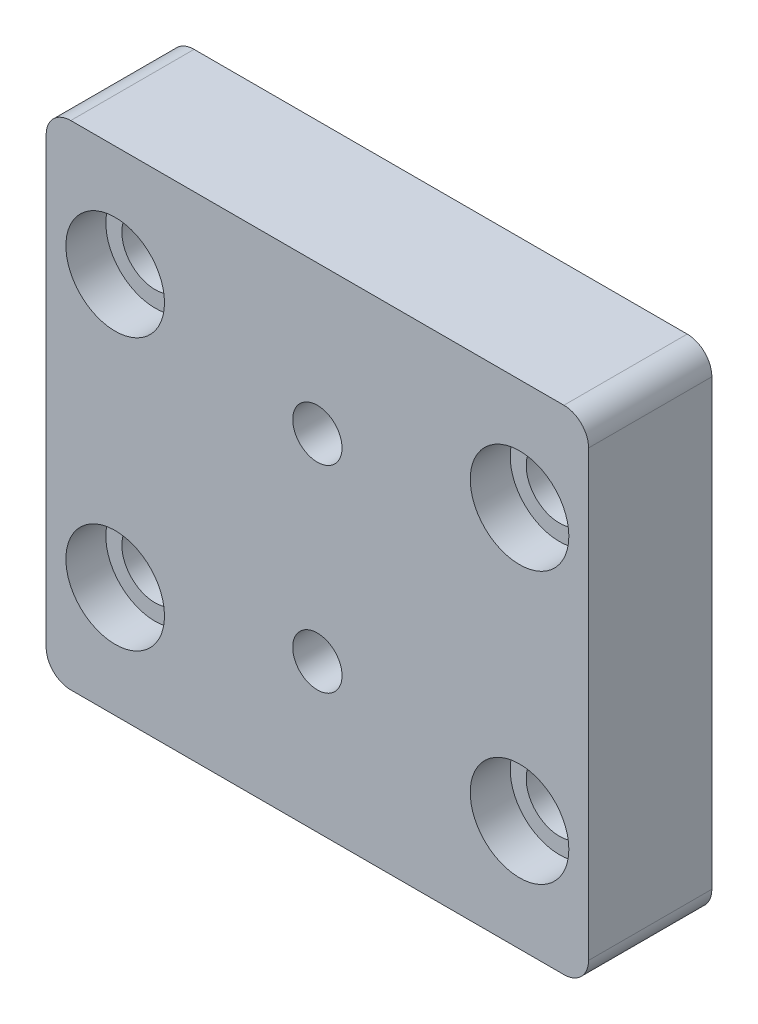
SolidWorks part; units mm, degrees
material "Masterteil Geometrie"
ref_plane "Vorne" through (0, 0, 0) normal (0, 0, 1) x (1, 0, 0)
ref_plane "Oben" through (0, 0, 0) normal (0, 1, 0) x (1, 0, 0)
ref_plane "Rechts" through (0, 0, 0) normal (1, 0, 0) x (0, 0, -1)
sketch "Skizze1" plane through (0, 0, 0) normal (0, 0, 1) x (1, 0, 0)
  line L1 (-55, -50) -> (55, -50)
  line L2 (-55, -50) -> (-55, 50)
  line L3 (-55, 50) -> (55, 50)
  line L4 (55, -50) -> (55, 50)
  line L5 (-55, -50) -> (55, 50) construction
  line L6 (-55, 50) -> (55, -50) construction
  point P0 (0, 0)
  dimension "D1" = 100
  dimension "D2" = 110
extrude "Aufsatz-Linear austragen1" add sketch "Skizze1" along normal blind 25
fillet "Verrundung1" radius 5 4 edges at (-55, -50, 12.5) (55, -50, 12.5) (-55, 50, 12.5) (55, 50, 12.5)
hole_wizard "Stirnsenkung für M12 Zylinderschraube mit Innensechskant1" positions "Skizze2" profile "Skizze3" counterbore size "M12" standard "Gabler-Normteile" end condition through all
sketch "Skizze2" plane through (0, 0, 25) normal (0, 0, 1) x (1, 0, 0)
  line L0 (-41, 27.5) -> (41, -27.5) construction
  line L1 (41, -27.5) -> (-41, -27.5) construction
  line L2 (-41, -27.5) -> (41, 27.5) construction
  point P0 (-41, 27.5)
  point P2 (41, 27.5)
  point P4 (41, -27.5)
  point P6 (-41, -27.5)
  point P16 (0, 0)
  point P20 (0, 0)
  point P22 (0, -27.5)
  dimension "D1" = 55
  dimension "D2" = 82
sketch "Skizze3" plane through (-41, 27.5, 25) normal (1, 0, 0) x (0, -1, 0)
  line L0 (0, 0) -> (0, 25)
  line L1 (0, 25) -> (6.75, 25)
  line L3 (6.75, 25) -> (6.75, 8.1)
  line L4 (6.75, 8.1) -> (10, 8.1)
  line L5 (10, 8.1) -> (10, 0)
  line L7 (10, 0) -> (0, 0)
  line L11 (0, -6.35) -> (0, 107.95) construction
  dimension "Bohrerdurchmesser" = 13.5
  dimension "Bohrungstiefe" = 25
  dimension "Senkdurchmesser2" = 20
  dimension "Senktiefe2" = 8.1
hole_wizard "Ø10.0mm Stiftloch1" positions "Skizze4" profile "Skizze5" hole size "Ø10.0" standard "Gabler-Normteile"
sketch "Skizze4" plane through (0, 0, 25) normal (0, 0, 1) x (1, 0, 0)
  line L0 (-50, -50) -> (50, -50) construction
  point P0 (0, 20)
  point P2 (0, -20)
  dimension "D1" = 30
  dimension "D2" = 40
sketch "Skizze5" plane through (0, 20, 25) normal (1, 0, 0) x (0, -1, 0)
  line L0 (0, 0) -> (0, 13.0043)
  line L1 (0, 13.0043) -> (5, 10)
  line L2 (5, 10) -> (5, 0)
  line L5 (5, 0) -> (0, 0)
  line L10 (0, 13.0043) -> (-5, 10) construction
  line L11 (0, -6.35) -> (0, 107.95) construction
  dimension "Bohrerdurchmesser" = 10
  dimension "Bohrungstiefe" = 10
  dimension "Spitzenwinkel" = 118
